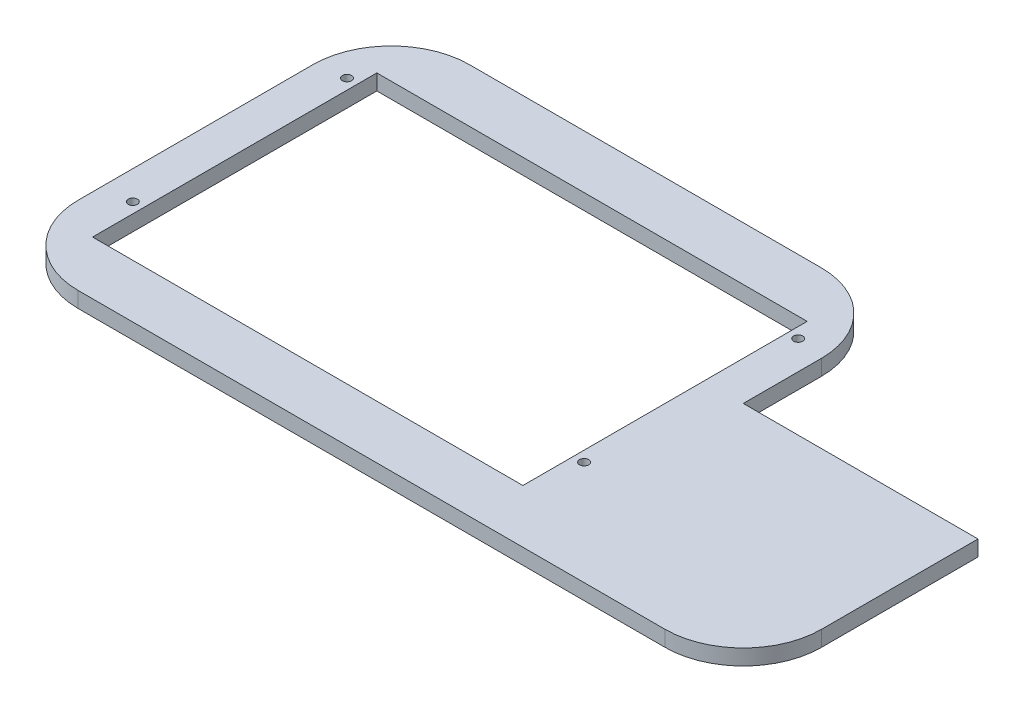
SolidWorks part; units mm, degrees
ref_plane "Front Plane" through (0, 0, 0) normal (0, 0, 1) x (1, 0, 0)
ref_plane "Top Plane" through (0, 0, 0) normal (0, 1, 0) x (1, 0, 0)
ref_plane "Right Plane" through (0, 0, 0) normal (1, 0, 0) x (0, 0, -1)
sketch "Sketch1" plane through (0, 0, 0) normal (0, 1, 0) x (1, 0, 0)
  line L0 (0, 75) -> (285, 75) construction
  line L1 (30, 150) -> (165, 150)
  line L2 (0, 120) -> (0, 30)
  line L3 (30, 0) -> (255, 0)
  line L4 (285, 90) -> (285, 30)
  line L5 (97.5, 150) -> (97.5, 0) construction
  line L6 (195, 120) -> (195, 90)
  line L7 (195, 90) -> (285, 90)
  line L9 (15, 129.5) -> (180, 129.5)
  line L10 (15, 129.5) -> (15, 20.5)
  line L11 (15, 20.5) -> (180, 20.5)
  line L12 (180, 129.5) -> (180, 20.5)
  arc A0 (0, 30) -> (30, 0) centre (30, 30) ccw
  arc A1 (255, 0) -> (285, 30) centre (255, 30) ccw
  arc A2 (195, 120) -> (165, 150) centre (165, 120) ccw
  arc A3 (30, 150) -> (0, 120) centre (30, 120) ccw
  point P12 (0, 0)
  point P17 (195, 150)
  dimension "D3" = 90
  dimension "D6" = 165
  dimension "D5" = 30
  dimension "D1" = 285
  dimension "D2" = 150
  dimension "D4" = 60
  dimension "D7" = 109
extrude "Boss-Extrude1" add sketch "Sketch1" along normal blind 6
sketch "Sketch2" plane through (0, 0, 0) normal (0, 1, 0) x (1, 0, 0)
  line L0 (180, 129.5) -> (15, 129.5) construction
  line L1 (15, 81) -> (180, 81) construction
  line L2 (15, 129.5) -> (15, 20.5) construction
  line L4 (180, 20.5) -> (180, 129.5) construction
  line L6 (97.5, 129.5) -> (97.5, 20.5) construction
  line L7 (15, 20.5) -> (180, 20.5) construction
  circle A0 centre (184, 122.05) radius 1.75
  circle A1 centre (11, 122.05) radius 1.75
  circle A2 centre (184, 39.95) radius 1.75
  circle A3 centre (11, 39.95) radius 1.75
  point P0 (11, 122.05)
  point P9 (0, 0)
  point P16 (0, 0)
  point P17 (0, 0)
  point P18 (0, 0)
  point P21 (0, 0)
  dimension "D2" = 4
  dimension "D3" = 48.5
  dimension "D4" = 1.75
  dimension "D1" = 7.45
extrude "Cut-Extrude4" cut sketch "Sketch2" along normal through all
